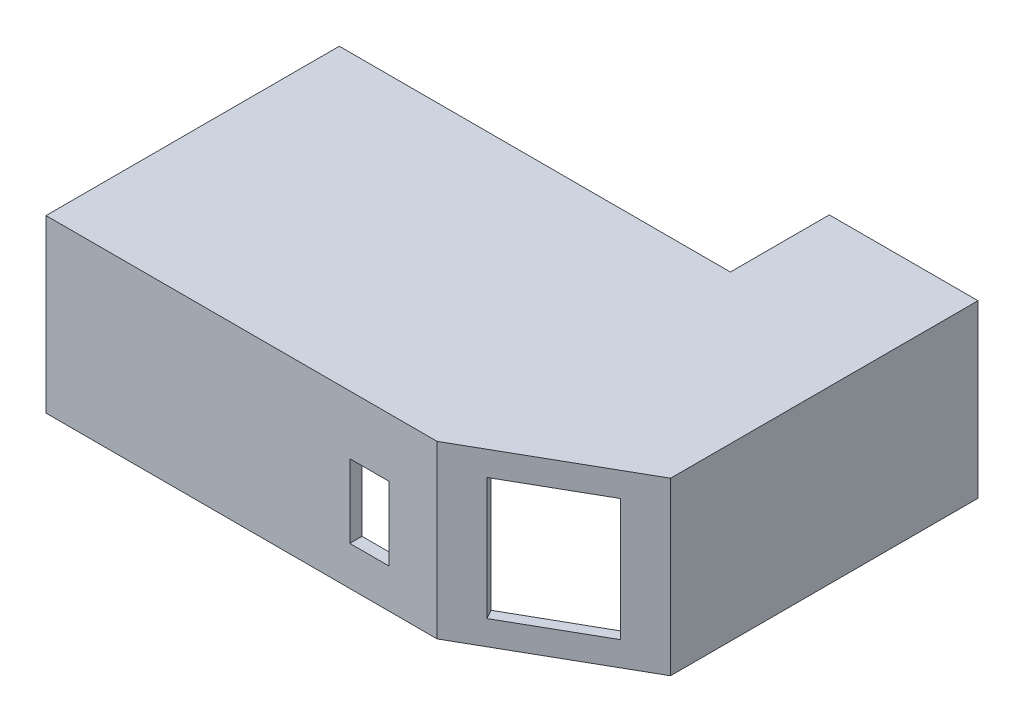
SolidWorks part; units mm, degrees
ref_plane "Ön Düzlem" through (0, 0, 0) normal (0, 0, 1) x (1, 0, 0)
ref_plane "Üst Düzlem" through (0, 0, 0) normal (0, 1, 0) x (1, 0, 0)
ref_plane "Sağ Düzlem" through (0, 0, 0) normal (1, 0, 0) x (0, 0, -1)
sketch "Çizim1" plane through (0, 0, 0) normal (0, 1, 0) x (1, 0, 0)
  line L0 (80, 0) -> (110.414, 17.3488)
  line L1 (0, 0) -> (80, 0)
  line L2 (0, 0) -> (0, 60)
  line L3 (0, 60) -> (80, 60)
  line L5 (110.414, 17.3488) -> (110.414, 60)
  line L6 (110.414, 60) -> (110.414, 80.241)
  line L7 (110.414, 80.241) -> (80, 80.241)
  line L8 (80, 80.241) -> (80, 60)
  dimension "D1" = 80
  dimension "D2" = 60
extrude "Yükseklik-Ekstrüzyon1" add sketch "Çizim1" along normal blind 35
sketch "Çizim5" plane through (0, 0, 0) normal (0, -1, 0) x (-1, 0, 0)
  line L1 (-2.5, 2.5) -> (-80, 2.5)
  line L2 (-2.5, 2.5) -> (-2.5, 57.5)
  line L3 (-2.5, 57.5) -> (-80.0135, 57.5)
  line L5 (-107.914, 18.3462) -> (-107.914, 77.741)
  line L6 (-107.914, 77.741) -> (-82.5, 77.741)
  line L7 (-82.5, 77.741) -> (-82.5, 57.5)
  line L8 (-82.5, 57.5) -> (-80.0135, 57.5)
  line L9 (0, 60) -> (0, 0) construction
  line L10 (-80, 60) -> (0, 60) construction
  line L11 (-80, 80.241) -> (-80, 60) construction
  line L12 (-110.414, 80.241) -> (-80, 80.241) construction
  line L13 (-110.414, 17.3488) -> (-110.414, 80.241) construction
  line L15 (0, 0) -> (-80, 0) construction
  line L16 (-80, 2.5) -> (-107.914, 18.3462)
  dimension "D1" = 2.5
  dimension "D2" = 2.5
  dimension "D3" = 2.5
  dimension "D4" = 2.5
  dimension "D5" = 2.5
  dimension "D7" = 2.5
extrude "Kes-Ekstrüzyon2" cut sketch "Çizim5" against normal blind 32.5 contours L1 L16 L5 L6 L7 L8 L3 L2
sketch "Çizim6" plane through (19.64, 0, 34.4307) normal (0.4955, 0, 0.8686) x (0.8686, 0, -0.4955)
  line L0 (69.4896, 35) -> (69.4896, 0) construction
  line L1 (76.9896, 30) -> (96.9896, 30)
  line L2 (76.9896, 30) -> (76.9896, 5)
  line L3 (76.9896, 5) -> (96.9896, 5)
  line L4 (96.9896, 30) -> (96.9896, 5)
  line L9 (69.4896, 35) -> (104.5037, 35) construction
  dimension "D1" = 25
  dimension "D2" = 20
  dimension "D3" = 7.5
  dimension "D4" = 5
extrude "Kes-Ekstrüzyon3" cut sketch "Çizim6" against normal blind 12.5
sketch "Çizim7" plane through (0, 0, -80.241) normal (0, 0, -1) x (-1, 0, 0)
  line L0 (-110.414, 0) -> (-80, 0) construction
  line L2 (-110.414, 35) -> (-110.414, 0) construction
  circle A0 centre (-97.414, 17.5) radius 3.5
  dimension "D3" = 7
  dimension "D1" = 17.5
  dimension "D2" = 13
extrude "Kes-Ekstrüzyon4" cut sketch "Çizim7" against normal blind 12.5
sketch "Çizim8" plane through (0, 0, 0) normal (0, 0, 1) x (1, 0, 0)
  line L0 (0, 35) -> (80, 35) construction
  line L1 (62.1549, 23) -> (70.1549, 23)
  line L2 (62.1549, 23) -> (62.1549, 8)
  line L3 (62.1549, 8) -> (70.1549, 8)
  line L4 (70.1549, 23) -> (70.1549, 8)
  dimension "D1" = 8
  dimension "D2" = 15
  dimension "D3" = 12
extrude "Kes-Ekstrüzyon5" cut sketch "Çizim8" against normal blind 12.5
